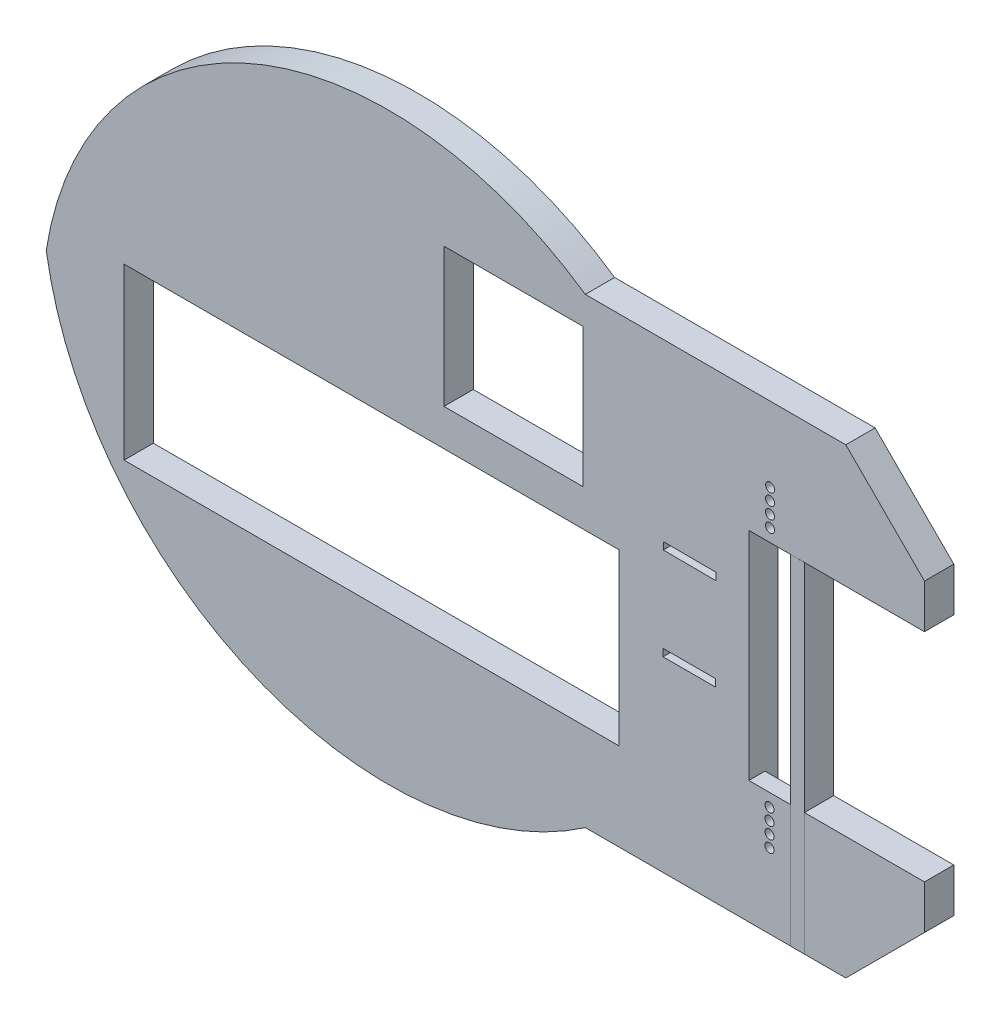
SolidWorks part; units mm, degrees
ref_plane "Front Plane" through (0, 0, 0) normal (0, 0, 1) x (1, 0, 0)
ref_plane "Top Plane" through (0, 0, 0) normal (0, 1, 0) x (1, 0, 0)
ref_plane "Right Plane" through (0, 0, 0) normal (1, 0, 0) x (0, 0, -1)
sketch "Sketch1" plane through (0, 0, 0) normal (0, 0, 1) x (1, 0, 0)
  line L1 (0, 0) -> (0, -37)
  line L2 (0, 37) -> (60, 37)
  line L3 (0, -37) -> (60, -37)
  line L4 (60, 37) -> (60, 52)
  line L5 (60, -37) -> (60, -52)
  line L6 (60, 52) -> (33.1299, 78.8701)
  line L7 (33.1299, 78.8701) -> (-55.8501, 78.8701)
  line L8 (60, -52) -> (33.1299, -78.8701)
  line L9 (33.1299, -78.8701) -> (-55.8501, -78.8701)
  line L10 (-55.8501, 78.8701) -> (-55.8501, 156.9436) construction
  line L11 (-55.8501, 156.9436) -> (-55.8501, -275.005) construction
  line L22 (0, 37) -> (0, 0)
  line L24 (-123.0632, 99.8019) -> (-270.1361, 99.8019) construction
  line L25 (-123.0632, 18.6512) -> (-123.0632, 134.1641) construction
  line L26 (-123.0632, -18.5763) -> (-123.0632, -116.9478) construction
  line L27 (-123.0632, -99.7887) -> (-269.8976, -99.7887) construction
  arc A7 (-239.9999, -0.1587) -> (-55.8501, 78.8701) centre (-123.0632, -18.5763) cw
  arc A8 (-55.8501, -78.8701) -> (-239.9999, -0.1587) centre (-123.0632, 18.6512) cw
  dimension "D11" = 199.5908
  dimension "D12" = 240
  dimension "D10" = 157.7401
  dimension "D1" = 37
  dimension "D2" = 37
  dimension "D3" = 60
  dimension "D4" = 15
  dimension "D5" = 15
  dimension "D6" = 135
  dimension "D7" = 38
  dimension "D8" = 38
  dimension "D9" = 135
  dimension "D15" = 88.98
  dimension "D16" = 88.98
extrude "Boss-Extrude1" add sketch "Sketch1" along normal blind 10 and the other way blind 0.01
sketch "Sketch3" plane through (0, 0, 10) normal (0, 0, 1) x (1, 0, 0)
  line L0 (33.1299, 78.8701) -> (-55.8501, 78.8701) construction
  line L1 (-38, 78.8701) -> (0, 78.8701)
  line L2 (-38, 78.8701) -> (-38, 24.8701)
  line L3 (-38, 24.8701) -> (0, 24.8701)
  line L4 (0, 78.8701) -> (0, 24.8701)
  dimension "D1" = 54
extrude "Cut-Extrude1" [suppressed] cut sketch "Sketch3" against normal blind 3 contours L2 L1 L4 L3
sketch "Sketch5" plane through (0, 0, 10) normal (0, 0, 1) x (1, 0, 0)
  line L0 (-55.8501, -78.8701) -> (33.1299, -78.8701) construction
  line L1 (-38, -24.8701) -> (0, -24.8701)
  line L2 (-38, -24.8701) -> (-38, -78.8701)
  line L3 (-38, -78.8701) -> (0, -78.8701)
  line L4 (0, -24.8701) -> (0, -78.8701)
  dimension "D1" = 54
extrude "Cut-Extrude3" [suppressed] cut sketch "Sketch5" against normal blind 3
sketch "Sketch7" plane through (0, 0, 10) normal (0, 0, 1) x (1, 0, 0)
  line L1 (-213.4131, 9.0562) -> (-44.4131, 9.0562)
  line L2 (-213.4131, 9.0562) -> (-213.4131, -48.9438)
  line L3 (-213.4131, -48.9438) -> (-44.4131, -48.9438)
  line L4 (-44.4131, 9.0562) -> (-44.4131, -48.9438)
  point P4 (0, 0)
  point P5 (0, 0)
  dimension "D1" = 58
  dimension "D2" = 169
extrude "Cut-Extrude4" cut sketch "Sketch7" against normal through all
sketch "Sketch8" plane through (0, 0, 10) normal (0, 0, 1) x (1, 0, 0)
  line L1 (-162.9927, 67.8133) -> (-84.7927, 67.8133)
  line L2 (-162.9927, 67.8133) -> (-162.9927, 10.3133)
  line L3 (-162.9927, 10.3133) -> (-84.7927, 10.3133)
  line L4 (-84.7927, 67.8133) -> (-84.7927, 10.3133)
  dimension "D1" = 78.2
  dimension "D2" = 57.5
extrude "Cut-Extrude5" [suppressed] cut sketch "Sketch8" against normal blind 3
sketch "Sketch9" plane through (0, 0, 10) normal (0, 0, 1) x (1, 0, 0)
  line L1 (-195, 36) -> (-176, 36)
  line L2 (-195, 36) -> (-195, 20)
  line L3 (-195, 20) -> (-176, 20)
  line L4 (-176, 36) -> (-176, 20)
  line L5 (-95.7317, 17.4542) -> (-82.493, 17.4542)
  line L6 (-95.7317, 17.4542) -> (-95.7317, 7.0108)
  line L7 (-95.7317, 7.0108) -> (-82.493, 7.0108)
  line L8 (-82.493, 17.4542) -> (-82.493, 7.0108)
  line L9 (-131.8867, -50.9252) -> (-116.9909, -50.9252)
  line L10 (-131.8867, -50.9252) -> (-131.8867, -65.1638)
  line L11 (-131.8867, -65.1638) -> (-116.9909, -65.1638)
  line L12 (-116.9909, -50.9252) -> (-116.9909, -65.1638)
extrude "Boss-Extrude2" [suppressed] add sketch "Sketch9" along normal blind 20.3
sketch "Sketch15" plane through (0, 0, 10) normal (0, 0, 1) x (1, 0, 0)
  line L0 (0, -37) -> (0, 37) construction
  line L1 (-20, 25.2016) -> (0, 25.2016)
  line L2 (-20, 25.2016) -> (-20, -24.7984)
  line L3 (-20, -24.7984) -> (0, -24.7984)
  line L4 (0, 25.2016) -> (0, -24.7984)
  point P6 (0, 0)
  dimension "D1" = 50
  dimension "D2" = 20
extrude "Boss-Extrude3" [suppressed] add sketch "Sketch15" along normal blind 20.3
sketch "Sketch16" plane through (0, 0, 10) normal (0, 0, 1) x (1, 0, 0)
  line L1 (-232.4208, 4) -> (-224.8235, 4)
  line L2 (-232.4208, 4) -> (-232.4208, -4)
  line L3 (-232.4208, -4) -> (-224.8235, -4)
  line L4 (-224.8235, 4) -> (-224.8235, -4)
  line L9 (-134.6881, 94.0493) -> (-144.6881, 94.0493)
  line L10 (-134.6881, 94.0493) -> (-134.6881, 84.6493)
  line L11 (-134.6881, 84.6493) -> (-144.6881, 84.6493)
  line L12 (-144.6881, 94.0493) -> (-144.6881, 84.6493)
  line L13 (-61.6779, 70.3488) -> (-70.3779, 70.3488)
  line L14 (-61.6779, 70.3488) -> (-61.6779, 61.8488)
  line L15 (-61.6779, 61.8488) -> (-70.3779, 61.8488)
  line L16 (-70.3779, 70.3488) -> (-70.3779, 61.8488)
  line L17 (-65.9779, -61.6233) -> (-75.3779, -61.6233)
  line L18 (-65.9779, -61.6233) -> (-65.9779, -70.9233)
  line L19 (-65.9779, -70.9233) -> (-75.3779, -70.9233)
  line L20 (-75.3779, -61.6233) -> (-75.3779, -70.9233)
  line L21 (-134.6881, -83.6815) -> (-144.6881, -83.6815)
  line L22 (-134.6881, -83.6815) -> (-134.6881, -92.9815)
  line L23 (-134.6881, -92.9815) -> (-144.6881, -92.9815)
  line L24 (-144.6881, -83.6815) -> (-144.6881, -92.9815)
  point P4 (0, 0)
  point P5 (0, 0)
  point P6 (0, 0)
  point P7 (0, 0)
extrude "Boss-Extrude4" [suppressed] add sketch "Sketch16" along normal blind 30
sketch "Sketch17" plane through (0, 0, 0) normal (0, 0, 1) x (1, 0, 0)
  circle A1 centre (-228.4208, 0) radius 2.55
  circle A2 centre (-139.6881, 89.6493) radius 3.5
  circle A3 centre (-65.8779, 66.3488) radius 3.5
  circle A4 centre (-69.8779, -66.6233) radius 3.5
  circle A5 centre (-139.6881, -88.6815) radius 3.5
  point P0 (0, 0)
extrude "Cut-Extrude17" [suppressed] cut sketch "Sketch17" along normal through all
sketch "Sketch18" plane through (0, 0, 10) normal (0, 0, 1) x (1, 0, 0)
  line L1 (-104.1245, 69) -> (-56.7245, 69)
  line L2 (-104.1245, 69) -> (-104.1245, 21.6)
  line L3 (-104.1245, 21.6) -> (-56.7245, 21.6)
  line L4 (-56.7245, 69) -> (-56.7245, 21.6)
  point P4 (0, 0)
  dimension "D1" = 47.4
  dimension "43.4" = 47.4
extrude "Cut-Extrude18" cut sketch "Sketch18" against normal through all
sketch "Sketch20" plane through (0, 0, 0) normal (0, 0, 1) x (1, 0, 0)
  circle A0 centre (-185.9471, 27.1121) radius 5
  circle A1 centre (-124.7094, -57.6129) radius 5
  circle A2 centre (-88.8879, 12.7504) radius 4
extrude "Cut-Extrude20" [suppressed] cut sketch "Sketch20" along normal through all
sketch "Sketch21" plane through (0, 0, 0) normal (1, 0, 0) x (0, 0, -1)
  line L0 (-3.8276, 29.0855) -> (-3.8276, -37.1575) construction
  line L1 (-6.4886, 28.3852) -> (-6.4886, -37.2976) construction
  line L2 (-5.0881, 28.1051) -> (-5.0881, -37.5777) construction
  line L3 (-11.99, 2.3019) -> (-12.0559, -4.1532) construction
  line L4 (-9.4916, 2.2764) -> (-9.5574, -4.1787)
  line L5 (-14.4885, 2.3274) -> (-14.5544, -4.1277)
  circle A0 centre (-19.3619, 12.3718) radius 9
  circle A1 centre (-19.2654, -14.6282) radius 9
  arc A2 (-9.4916, 2.2764) -> (-14.4885, 2.3274) centre (-11.99, 2.3019) ccw
  arc A3 (-14.5544, -4.1277) -> (-9.5574, -4.1787) centre (-12.0559, -4.1532) ccw
  point P12 (-12.023, -0.9256)
  dimension "D1" = 18
  dimension "D2" = 18
  dimension "D3" = 27
extrude "Cut-Extrude21" [suppressed] cut sketch "Sketch21" against normal up to surface (20 mm away)
sketch "Sketch25" plane through (0, 0, 10) normal (0, 0, 1) x (1, 0, 0)
  line L1 (-173.6964, 70.8495) -> (-165.5964, 70.8495)
  line L2 (-173.6964, 70.8495) -> (-173.6964, 11.3495)
  line L3 (-173.6964, 11.3495) -> (-165.5964, 11.3495)
  line L4 (-165.5964, 70.8495) -> (-165.5964, 11.3495)
  dimension "D1" = 8.1
  dimension "D2" = 59.5
extrude "Boss-Extrude5" [suppressed] add sketch "Sketch25" along normal blind 3.5
sketch "Sketch26" [suppressed] plane through (0, 11.3495, 0) normal (0, -1, 0) x (1, 0, 0)
  line L0 (-172.679, 10.0037) -> (-152.674, 9.9893) construction
  line L1 (-152.674, 9.9893) -> (-152.6595, 14.6073) construction
  line L2 (-165.5928, 10.0085) -> (-173.4128, 10.0085)
  line L3 (-173.4128, 10.0085) -> (-173.4128, 12.4083)
  line L4 (-173.4128, 12.4083) -> (-165.5928, 12.4083)
  line L5 (-165.5928, 12.4083) -> (-165.5928, 10.0083)
  line M7 (-165.5964, 10) -> (-165.5964, 13.5)
extrude "Cut-Extrude24" [suppressed] cut sketch "Sketch26" against normal up to surface (59.5 mm away) contours L4 L3 L2 M7
sketch "Sketch28" plane through (0, -78.8701, 0) normal (0, -1, 0) x (1, 0, 0)
  line L1 (14.2266, 10.0076) -> (18.9795, 10.0076)
  line L2 (14.2266, 10.0076) -> (14.2266, 0.0598)
  line L3 (14.2266, 0.0598) -> (18.9795, 0.0598)
  line L4 (18.9795, 10.0076) -> (18.9795, 0.0598)
extrude "Boss-Extrude6" add sketch "Sketch28" against normal up to surface (115.8701 mm away) up to face at (30, 37, 4.995)
sketch "Sketch30" plane through (0, 0, -0.01) normal (0, 0, -1) x (-1, 0, 0)
  line L0 (0.5881, -0.0011) -> (-26.6848, -0.0585) construction
  line L1 (0, -62) -> (-14.12, -62)
  line L2 (0, -62) -> (0, -37)
  line L3 (0, -37) -> (-14.12, -37)
  line L4 (-14.12, -62) -> (-14.12, -37)
  line L5 (-14.3807, 61.9354) -> (-14.2755, 36.9356)
  line L6 (-0.1557, 36.995) -> (-14.2755, 36.9356)
  line L7 (-0.2608, 61.9948) -> (-0.1557, 36.995)
  line L8 (-0.2608, 61.9948) -> (-14.3807, 61.9354)
  dimension "D1" = 25
  dimension "D2" = 14.12
extrude "Cut-Extrude25" cut sketch "Sketch30" against normal blind 4.5
sketch "Sketch33" plane through (0, 0, -0.01) normal (0, 0, -1) x (-1, 0, 0)
  line L0 (0, 0) -> (-115.8951, -0.2361) construction
  circle A0 centre (-7.06, -53.4) radius 1.55
  circle A1 centre (-7.06, -49.4) radius 1.55
  circle A2 centre (-7.06, -45.4) radius 1.55
  circle A3 centre (-7.06, -41.4) radius 1.55
  circle A4 centre (-7.2286, 41.3709) radius 1.55
  circle A5 centre (-7.2449, 45.3709) radius 1.55
  circle A6 centre (-7.2612, 49.3708) radius 1.55
  circle A7 centre (-7.2775, 53.3708) radius 1.55
  dimension "D1" = 4
extrude "Cut-Extrude26" cut sketch "Sketch33" against normal up to surface (10.01 mm away) up to face at (-128.9131, -19.9438, 10)
sketch "Sketch34" plane through (0, 0, 10) normal (0, 0, 1) x (1, 0, 0)
  line L0 (0, 0) -> (85.4359, -0.2266) construction
  line L1 (53.8089, -34.3247) -> (61.9289, -40.2214)
  line L2 (53.8089, -34.3247) -> (57.1772, -29.6864)
  line L3 (61.9289, -40.2214) -> (65.2973, -35.5831)
  line L4 (57.1772, -29.6864) -> (65.2973, -35.5831)
  line L5 (62.1414, 39.8924) -> (65.4851, 35.2362)
  line L6 (57.3338, 29.3826) -> (65.4851, 35.2362)
  line L7 (53.9902, 34.0388) -> (57.3338, 29.3826)
  line L8 (53.9902, 34.0388) -> (62.1414, 39.8924)
extrude "Cut-Extrude27" [suppressed] cut sketch "Sketch34" against normal through all
sketch "Sketch36" [suppressed] plane through (0, 0, 7) normal (0, 0, 1) x (1, 0, 0)
  line L0 (0, 0) -> (106.9048, -0.1896) construction
  line L1 (0.2795, 78.8146) -> (0.2724, 76.8146)
  line L2 (0, -78.8151) -> (-38, -78.8151)
  line L3 (0, -78.8151) -> (0, -76.8151)
  line L4 (0, -76.8151) -> (-38, -76.8151)
  line L5 (-38, -78.8151) -> (-38, -76.8151)
  line L6 (-37.7202, 78.9494) -> (-37.7273, 76.9494)
  line L7 (0.2724, 76.8146) -> (-37.7273, 76.9494)
  line L8 (0.2795, 78.8146) -> (-37.7202, 78.9494)
  dimension "D1" = 2
extrude "Boss-Extrude7" [suppressed] add sketch "Sketch36" along normal blind 37
sketch "Sketch39" [suppressed] plane through (0, -78.8151, 0) normal (0, -1, 0) x (1, 0, 0)
  line L1 (-46.4365, 25) -> (22.9075, 25) construction
  line L4 (31.9978, 332) -> (-461.8231, 332) construction
  circle A1 centre (-19, 19) radius 6
  circle A2 centre (-34.4996, 25.0106) radius 1.55
  circle A3 centre (-3.5639, 24.9888) radius 1.55
  circle A4 centre (-28.8192, 37.0106) radius 1.55
  circle A5 centre (-9.1774, 36.9888) radius 1.55
  circle A6 centre (-28.82, 13.0106) radius 1.55
  circle A7 centre (-9.2305, 12.9888) radius 1.55
  point P18 (6.9989, 178.85)
  dimension "D1" = 12
  dimension "D5" = 12
  dimension "D6" = 12
  dimension "D7" = 12
  dimension "D8" = 12
  dimension "D2" = 19
extrude "Cut-Extrude28" [suppressed] cut sketch "Sketch39" against normal up to surface (2 mm away)
sketch "Sketch42" [suppressed] plane through (0.2795, 78.8146, 0) normal (0.0035, 1, 0) x (1, -0.0035, 0)
  circle A7 centre (-19.2797, -19) radius 6
  circle A9 centre (-29.0701, -13) radius 1.55
  circle A10 centre (-3.7784, -25) radius 1.55
  circle A11 centre (-9.4641, -13) radius 1.55
  circle A12 centre (-34.7723, -25) radius 1.55
  circle A13 centre (-29.0965, -37) radius 1.55
  circle A14 centre (-9.4734, -37) radius 1.55
  dimension "D1" = 12
  dimension "D5" = 6
  dimension "D6" = 6
  dimension "D7" = 6
  dimension "D8" = 6
  dimension "D9" = 18
  dimension "D10" = 18
  dimension "D2" = 19
extrude "Cut-Extrude29" [suppressed] cut sketch "Sketch42" against normal up to surface (2 mm away)
sketch "Sketch44" plane through (0, 0, -0.01) normal (0, 0, -1) x (-1, 0, 0)
  line L0 (0, 1.929) -> (77.4591, 2.1222) construction
  line L5 (11.3033, -12.561) -> (29.3033, -12.561)
  line L6 (11.3033, -12.561) -> (11.3033, -15.071)
  line L7 (11.3033, -15.071) -> (29.3033, -15.071)
  line L8 (29.3033, -12.561) -> (29.3033, -15.071)
  line L13 (29.2307, 16.565) -> (29.2181, 19.075)
  line L14 (11.2184, 18.9852) -> (29.2181, 19.075)
  line L15 (11.2309, 16.4752) -> (11.2184, 18.9852)
  line L16 (11.2309, 16.4752) -> (29.2307, 16.565)
  point P2 (0, 0)
  point P5 (-0.6999, -3.0216)
  dimension "D1" = 2.51
  dimension "D2" = 18
  dimension "D3" = 17
extrude "Cut-Extrude30" cut sketch "Sketch44" against normal up to surface (10.01 mm away) up to face at (5.51, -53.4, 10)
